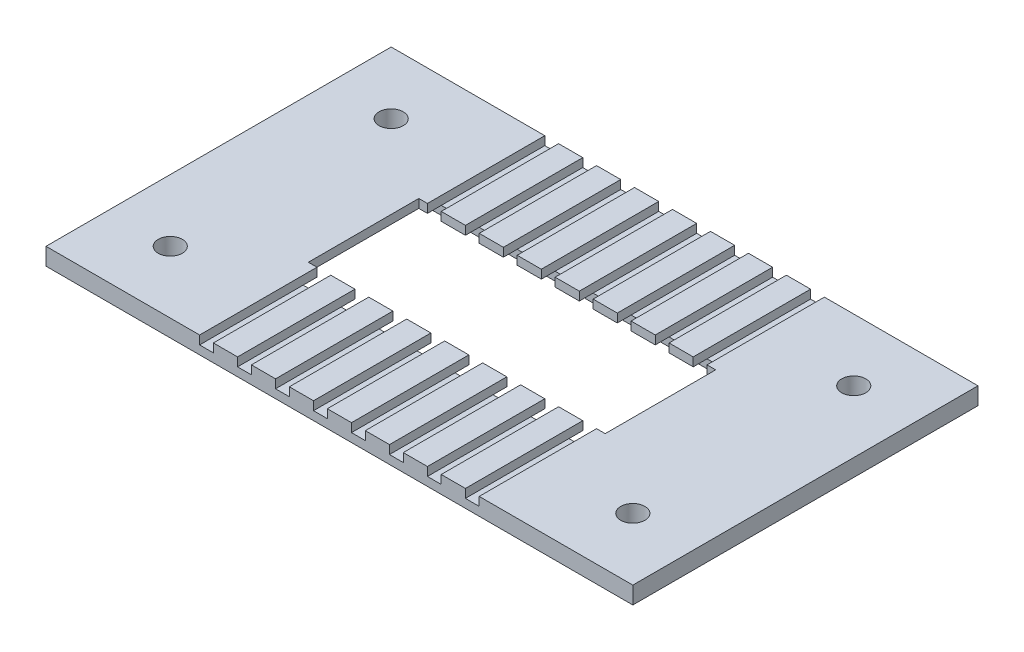
SolidWorks part; units mm, degrees
ref_plane "Front Plane" through (0, 0, 0) normal (0, 0, 1) x (1, 0, 0)
ref_plane "Top Plane" through (0, 0, 0) normal (0, 1, 0) x (1, 0, 0)
ref_plane "Right Plane" through (0, 0, 0) normal (1, 0, 0) x (0, 0, -1)
sketch "Sketch1" plane through (0, 0, 0) normal (0, 1, 0) x (1, 0, 0)
  line L1 (42.5, -25) -> (-42.5, -25)
  line L2 (42.5, -25) -> (42.5, 25)
  line L3 (42.5, 25) -> (-42.5, 25)
  line L4 (-42.5, -25) -> (-42.5, 25)
  line L5 (42.5, -25) -> (-42.5, 25) construction
  line L6 (42.5, 25) -> (-42.5, -25) construction
  point P0 (0, 0)
extrude "Base Plate" add sketch "Sketch1" along normal blind 2.5
sketch "Sketch7" plane through (0, 2.5, 0) normal (0, 1, 0) x (1, 0, 0)
  line L2 (0, 0) -> (-11.5051, 0) construction
  line L3 (-42.5, 25) -> (-42.5, -25) construction
  line L4 (0, 13.9859) -> (0, 0) construction
  line L5 (42.5, 25) -> (-42.5, 25) construction
  circle A0 centre (-33.5, 16) radius 1.75
  circle A1 centre (-33.5, -16) radius 1.75
  circle A2 centre (33.5, -16) radius 1.75
  circle A3 centre (33.5, 16) radius 1.75
  dimension "D1" = 3.5
  dimension "D2" = 9
  dimension "D3" = 9
extrude "Scre Cut" cut sketch "Sketch7" against normal blind 5
sketch "Sketch13" plane through (0, 2.5, 0) normal (0, 1, 0) x (1, 0, 0)
  line L1 (-21.5, 8) -> (21.5, 8)
  line L2 (-21.5, 8) -> (-21.5, -8)
  line L3 (-21.5, -8) -> (21.5, -8)
  line L4 (21.5, 8) -> (21.5, -8)
  line L5 (-21.5, 8) -> (21.5, -8) construction
  line L6 (-21.5, -8) -> (21.5, 8) construction
  point P0 (0, 0)
  dimension "D1" = 43
  dimension "D2" = 16
extrude "Cut-Extrude1" cut sketch "Sketch13" against normal blind 10
sketch "Sketch15" plane through (-42.5, 0, -25) normal (0, -1, 0) x (1, 0, 0)
  line L0 (42.5, 0) -> (42.5, 50) construction
  line L1 (85, 0) -> (0, 0) construction
  line L2 (0, 0) -> (0, 50) construction
  line L3 (0, 25) -> (42.5, 25) construction
  circle A0 centre (9, 9) radius 5
  circle A1 centre (9, 41) radius 5
  circle A2 centre (76, 41) radius 5
  circle A3 centre (76, 9) radius 5
  dimension "D1" = 10
extrude "Boss-Extrude3" add sketch "Sketch15" along normal blind 4
sketch "Sketch18" plane through (0, 0, 0) normal (0, 1, 0) x (1, 0, 0)
  line L0 (0, 0) -> (0, -29.8583) construction
  line L2 (-49.7998, 0) -> (0, 0) construction
  circle A0 centre (-33.5, 16) radius 1.75
  circle A1 centre (-33.5, 16) radius 1.75 construction
  circle A2 centre (-33.5, -16) radius 1.75
  circle A3 centre (33.5, 16) radius 1.75
  circle A4 centre (33.5, -16) radius 1.75
extrude "Cut-Extrude4" cut sketch "Sketch18" against normal up to surface (4 mm away) up to face at (-33.5, -4, -21)
sketch "Sketch19" plane through (0, -4, 0) normal (0, -1, 0) x (1, 0, 0)
  line L0 (0, 0) -> (0, -22.785) construction
  line L1 (-33.5, -12.7091) -> (-36.35, -14.3546)
  line L2 (-36.35, -14.3546) -> (-36.35, -17.6454)
  line L3 (-36.35, -17.6454) -> (-33.5, -19.2909)
  line L4 (-33.5, -19.2909) -> (-30.65, -17.6454)
  line L5 (-30.65, -17.6454) -> (-30.65, -14.3546)
  line L6 (-30.65, -14.3546) -> (-33.5, -12.7091)
  line L7 (-30.65, 14.3546) -> (-33.5, 12.7091)
  line L8 (-38.1664, 0) -> (0, 0) construction
  line L9 (-30.65, 17.6454) -> (-30.65, 14.3546)
  line L10 (-33.5, 19.2909) -> (-30.65, 17.6454)
  line L11 (-36.35, 17.6454) -> (-33.5, 19.2909)
  line L12 (-36.35, 14.3546) -> (-36.35, 17.6454)
  line L13 (-33.5, 12.7091) -> (-36.35, 14.3546)
  line L14 (30.65, -14.3546) -> (33.5, -12.7091)
  line L15 (30.65, -17.6454) -> (30.65, -14.3546)
  line L16 (33.5, -19.2909) -> (30.65, -17.6454)
  line L17 (36.35, -17.6454) -> (33.5, -19.2909)
  line L18 (36.35, -14.3546) -> (36.35, -17.6454)
  line L19 (33.5, -12.7091) -> (36.35, -14.3546)
  line L20 (33.5, 12.7091) -> (36.35, 14.3546)
  line L21 (36.35, 14.3546) -> (36.35, 17.6454)
  line L22 (36.35, 17.6454) -> (33.5, 19.2909)
  line L23 (33.5, 19.2909) -> (30.65, 17.6454)
  line L24 (30.65, 17.6454) -> (30.65, 14.3546)
  line L25 (30.65, 14.3546) -> (33.5, 12.7091)
  circle A2 centre (-33.5, -16) radius 2.85 construction
  circle A3 centre (-33.5, 16) radius 2.85 construction
  circle A4 centre (33.5, -16) radius 2.85 construction
  circle A5 centre (33.5, 16) radius 2.85 construction
  dimension "D1" = 5.7
extrude "M3 Nut" cut sketch "Sketch19" against normal blind 3
sketch "Sketch21" plane through (0, 0, 0) normal (0, -1, 0) x (1, 0, 0)
  line L0 (-21.5, 8) -> (21.5, 8) construction
  line L1 (-21.5, 8) -> (21.5, 8)
  line L2 (21.5, 8) -> (21.5, -8) construction
  line L3 (-23.5, 10) -> (23.5, 10)
  line L6 (23.5, 10) -> (23.5, -10)
  line L8 (21.5, 8) -> (21.5, -8)
  line L9 (23.5, -10) -> (-23.5, -10)
  line L11 (21.5, -8) -> (-21.5, -8)
  line L14 (-21.5, -8) -> (-21.5, 8)
  line L16 (-23.5, -10) -> (-23.5, 10)
  dimension "D1" = 2
  dimension "D2" = 2
  dimension "D3" = 2
  dimension "D4" = 2
extrude "Cut-Extrude7" cut sketch "Sketch21" against normal blind 1.25
sketch "Sketch20" plane through (0, 0, -25) normal (0, 0, -1) x (-1, 0, 0)
  line L0 (-42.5, 2.5) -> (42.5, 2.5) construction
  line L1 (-5.5, 2.5) -> (-5.5, 1.5238) construction
  line L2 (-1.75, 2.5) -> (-3.75, 2.5)
  line L3 (-1.75, 2.5) -> (-1.75, 1.25)
  line L4 (-1.75, 1.25) -> (-3.75, 1.25)
  line L5 (-3.75, 2.5) -> (-3.75, 1.25)
  line L6 (-9.25, 2.5) -> (-7.25, 2.5)
  line L7 (0, 2.5) -> (0, 3.5097) construction
  line L8 (-11, 1.5238) -> (-11, 2.5) construction
  line L9 (-7.25, 2.5) -> (-7.25, 1.25)
  line L10 (-9.25, 1.25) -> (-7.25, 1.25)
  line L11 (-9.25, 2.5) -> (-9.25, 1.25)
  line L12 (-14.75, 2.5) -> (-14.75, 1.25)
  line L13 (-12.75, 2.5) -> (-14.75, 2.5)
  line L14 (-12.75, 1.25) -> (-14.75, 1.25)
  line L15 (-12.75, 2.5) -> (-12.75, 1.25)
  line L16 (-16.5, 2.5) -> (-16.5, 1.25) construction
  line L17 (-20.25, 2.5) -> (-18.25, 2.5)
  line L18 (-18.25, 2.5) -> (-18.25, 1.25)
  line L19 (-20.25, 1.25) -> (-18.25, 1.25)
  line L20 (-20.25, 2.5) -> (-20.25, 1.25)
  line L21 (18.25, 2.5) -> (18.25, 1.25)
  line L22 (20.25, 2.5) -> (18.25, 2.5)
  line L23 (20.25, 2.5) -> (20.25, 1.25)
  line L24 (20.25, 1.25) -> (18.25, 1.25)
  line L25 (12.75, 1.25) -> (14.75, 1.25)
  line L26 (14.75, 2.5) -> (14.75, 1.25)
  line L27 (12.75, 2.5) -> (14.75, 2.5)
  line L28 (12.75, 2.5) -> (12.75, 1.25)
  line L29 (9.25, 2.5) -> (9.25, 1.25)
  line L30 (9.25, 2.5) -> (7.25, 2.5)
  line L31 (9.25, 1.25) -> (7.25, 1.25)
  line L32 (7.25, 2.5) -> (7.25, 1.25)
  line L33 (1.75, 2.5) -> (3.75, 2.5)
  line L34 (3.75, 2.5) -> (3.75, 1.25)
  line L35 (1.75, 1.25) -> (3.75, 1.25)
  line L36 (1.75, 2.5) -> (1.75, 1.25)
  dimension "D1" = 1.25
  dimension "D2" = 2
  dimension "D3" = 1.75
  dimension "D4" = 1.75
  dimension "D5" = 1.75
  dimension "D6" = 1.75
extrude "Cut-Extrude8" cut sketch "Sketch20" against normal up to surface (50 mm away) up to face at (0, 1.25, 25)
